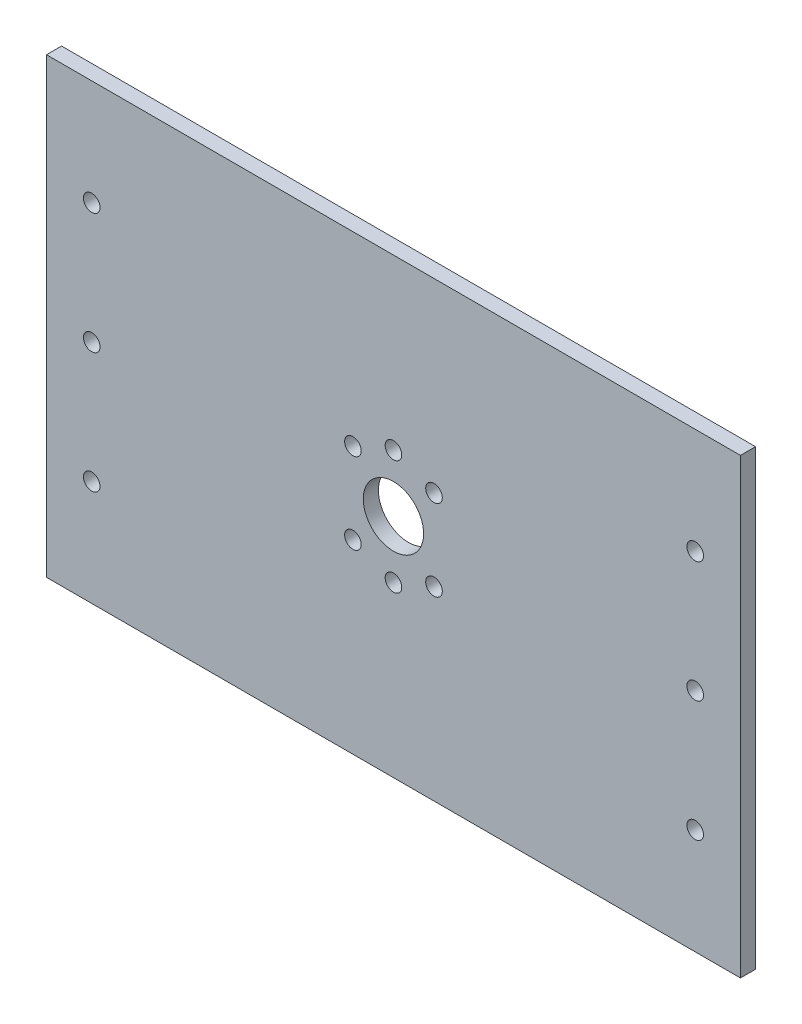
SolidWorks part; units mm, degrees
ref_plane "前视基准面" through (0, 0, 0) normal (0, 0, 1) x (1, 0, 0)
ref_plane "上视基准面" through (0, 0, 0) normal (0, 1, 0) x (1, 0, 0)
ref_plane "右视基准面" through (0, 0, 0) normal (1, 0, 0) x (0, 0, -1)
sketch "草图1" plane through (0, 0, 0) normal (0, 0, 1) x (1, 0, 0)
  line L0 (0, 75) -> (0, 0) construction
  line L1 (115, -75) -> (-115, -75)
  line L2 (115, -75) -> (115, 75)
  line L3 (115, 75) -> (-115, 75)
  line L4 (-115, -75) -> (-115, 75)
  line L5 (115, -75) -> (-115, 75) construction
  line L6 (115, 75) -> (-115, -75) construction
  line L7 (0, 0) -> (115, 0) construction
  line L8 (13.435, 13.435) -> (0, 0) construction
  line L9 (-100, 75) -> (-100, -75) construction
  circle A0 centre (0, 0) radius 19 construction
  circle A1 centre (0, 0) radius 10
  circle A2 centre (0, 19) radius 2.75
  circle A3 centre (13.435, 13.435) radius 2.75
  circle A4 centre (-13.435, 13.435) radius 2.75
  circle A5 centre (13.435, -13.435) radius 2.75
  circle A6 centre (-13.435, -13.435) radius 2.75
  circle A7 centre (0, -19) radius 2.75
  circle A8 centre (-100, 0) radius 2.75
  circle A9 centre (-100, 40) radius 2.75
  circle A10 centre (-100, -40) radius 2.75
  circle A11 centre (100, -40) radius 2.75
  circle A12 centre (100, 0) radius 2.75
  circle A13 centre (100, 40) radius 2.75
  point P0 (0, 0)
  dimension "D1" = 5.5
  dimension "D3" = 38
  dimension "D4" = 20
  dimension "D8" = 5.5
  dimension "D9" = 40
  dimension "D2" = 45
  dimension "D5" = 230
  dimension "D6" = 150
  dimension "D7" = 15
extrude "凸台-拉伸1" add sketch "草图1" along normal blind 5
